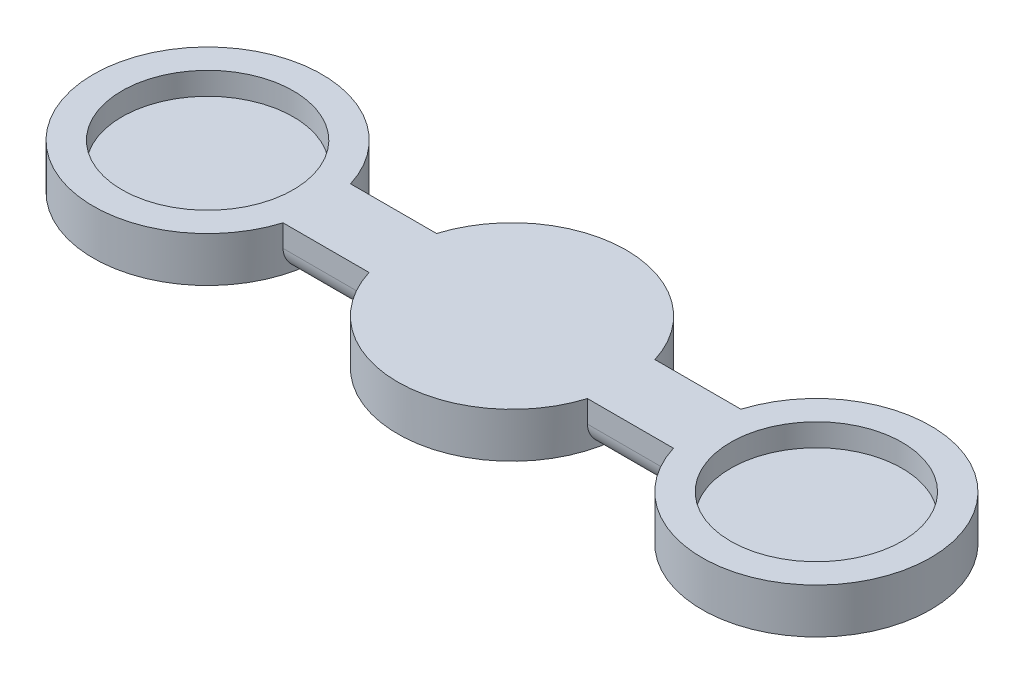
SolidWorks part; units mm, degrees
ref_plane "Front Plane" through (0, 0, 0) normal (0, 0, 1) x (1, 0, 0)
ref_plane "Top Plane" through (0, 0, 0) normal (0, 1, 0) x (1, 0, 0)
ref_plane "Right Plane" through (0, 0, 0) normal (1, 0, 0) x (0, 0, -1)
sketch "Sketch1" plane through (0, 0, 0) normal (0, 1, 0) x (1, 0, 0)
  circle A0 centre (0, 0) radius 12.7
  dimension "D1" = 25.4
extrude "Boss-Extrude1" add sketch "Sketch1" along normal blind 5
sketch "Sketch2" plane through (0, 5, 0) normal (0, 1, 0) x (1, 0, 0)
  line L1 (38.1, -3.75) -> (-38.1, -3.75)
  line L2 (38.1, -3.75) -> (38.1, 3.75)
  line L3 (38.1, 3.75) -> (-38.1, 3.75)
  line L4 (-38.1, -3.75) -> (-38.1, 3.75)
  line L5 (38.1, -3.75) -> (-38.1, 3.75) construction
  line L6 (38.1, 3.75) -> (-38.1, -3.75) construction
  point P0 (0, 0)
  dimension "D1" = 7.5
  dimension "D2" = 76.2
extrude "Boss-Extrude2" add sketch "Sketch2" against normal up to surface (5 mm away) up to face at (0, 0, 12.7)
sketch "Sketch3" plane through (0, 5, 0) normal (0, 1, 0) x (1, 0, 0)
  circle A0 centre (-33.8191, 0) radius 12.7
  dimension "D1" = 25.4
extrude "Boss-Extrude3" add sketch "Sketch3" against normal up to surface (5 mm away) up to face at (0, 0, 0)
sketch "Sketch4" plane through (0, 5, 0) normal (0, 1, 0) x (1, 0, 0)
  circle A0 centre (-33.8191, 0) radius 9.525
  arc A1 (-21.6854, 3.75) -> (-21.6854, -3.75) centre (-33.8191, 0) ccw construction
  dimension "D1" = 19.05
extrude "Cut-Extrude1" cut sketch "Sketch4" against normal blind 2.5
mirror "Mirror1" about plane through (0, 0, 0) normal (1, 0, 0) of "Cut-Extrude1", "Boss-Extrude3"
fillet "Fillet1" radius 2.54 4 edges at (16.9095, 0, 3.75) (-16.9095, 0, 3.75) (-16.9095, 0, -3.75) (16.9095, 0, -3.75)
